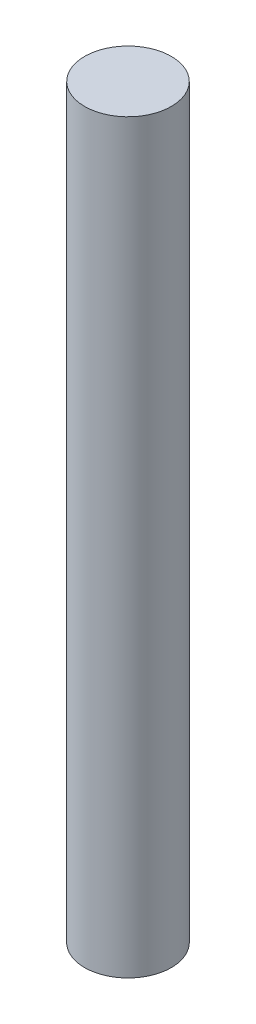
SolidWorks part; units mm, degrees
material "AISI 1020"
ref_plane "Front Plane" through (0, 0, 0) normal (0, 0, 1) x (1, 0, 0)
ref_plane "Top Plane" through (0, 0, 0) normal (0, 1, 0) x (1, 0, 0)
ref_plane "Right Plane" through (0, 0, 0) normal (1, 0, 0) x (0, 0, -1)
sketch "Sketch1" plane through (0, 0, 0) normal (0, 1, 0) x (1, 0, 0)
  circle A0 centre (0, 0) radius 2.5
  dimension "D1" = 5
extrude "Boss-Extrude1" add sketch "Sketch1" along normal blind 43
